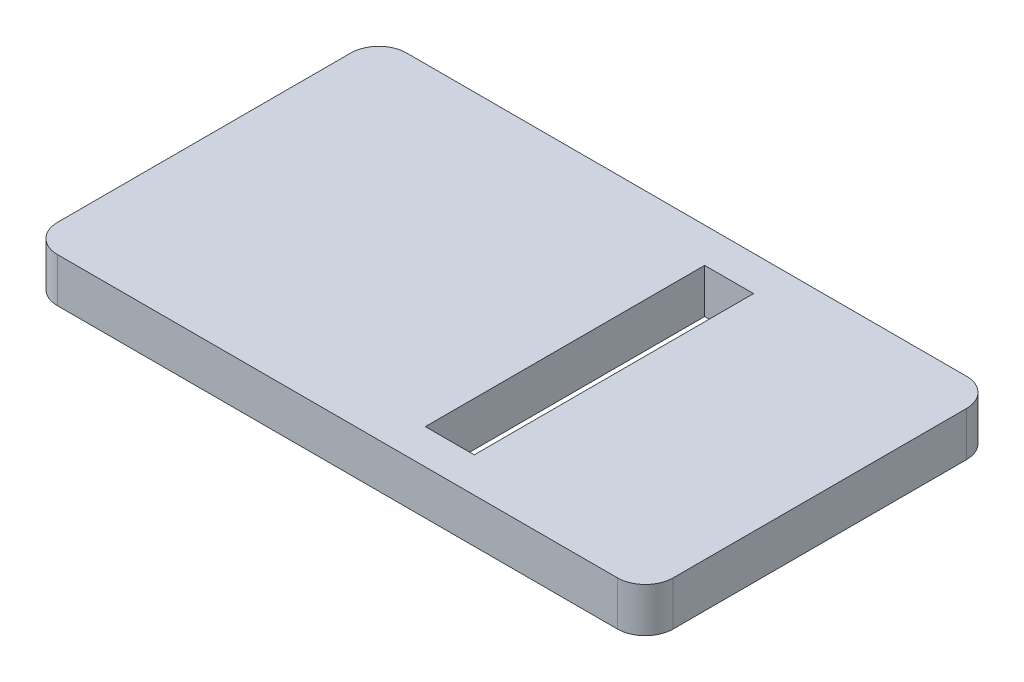
SolidWorks part; units mm, degrees
ref_plane "Front Plane" through (0, 0, 0) normal (0, 0, 1) x (1, 0, 0)
ref_plane "Top Plane" through (0, 0, 0) normal (0, 1, 0) x (1, 0, 0)
ref_plane "Right Plane" through (0, 0, 0) normal (1, 0, 0) x (0, 0, -1)
sketch "Sketch1" plane through (0, 0, 0) normal (0, 1, 0) x (1, 0, 0)
  line L0 (-44.09, 0) -> (44.09, 0) construction
  line L1 (-44.09, 25) -> (44.09, 25)
  line L2 (-44.09, 25) -> (-44.09, -25)
  line L3 (-44.09, -25) -> (44.09, -25)
  line L4 (44.09, 25) -> (44.09, -25)
  line L5 (-44.09, 25) -> (44.09, -25) construction
  line L6 (-44.09, -25) -> (44.09, 25) construction
  line L15 (14.59, 20) -> (14.59, -20) construction
  line L16 (7.59, 20) -> (14.59, 20)
  line L17 (7.59, 20) -> (7.59, -20)
  line L18 (7.59, -20) -> (14.59, -20)
  line L19 (14.59, 20) -> (14.59, -20)
  line L20 (7.59, 20) -> (14.59, 20) construction
  line L21 (7.59, -20) -> (7.59, 20) construction
  line L22 (14.59, -20) -> (7.59, -20) construction
  dimension "D1" = 0
  dimension "D2" = 0
  dimension "D3" = 0
  dimension "D4" = 50
  dimension "D5" = 88.18
  dimension "D6" = 0
extrude "Boss-Extrude1" add sketch "Sketch1" along normal blind 6.35
fillet "Fillet1" radius 4 4 edges at (-44.09, 3.175, 25) (-44.09, 3.175, -25) (44.09, 3.175, 25) (44.09, 3.175, -25)
